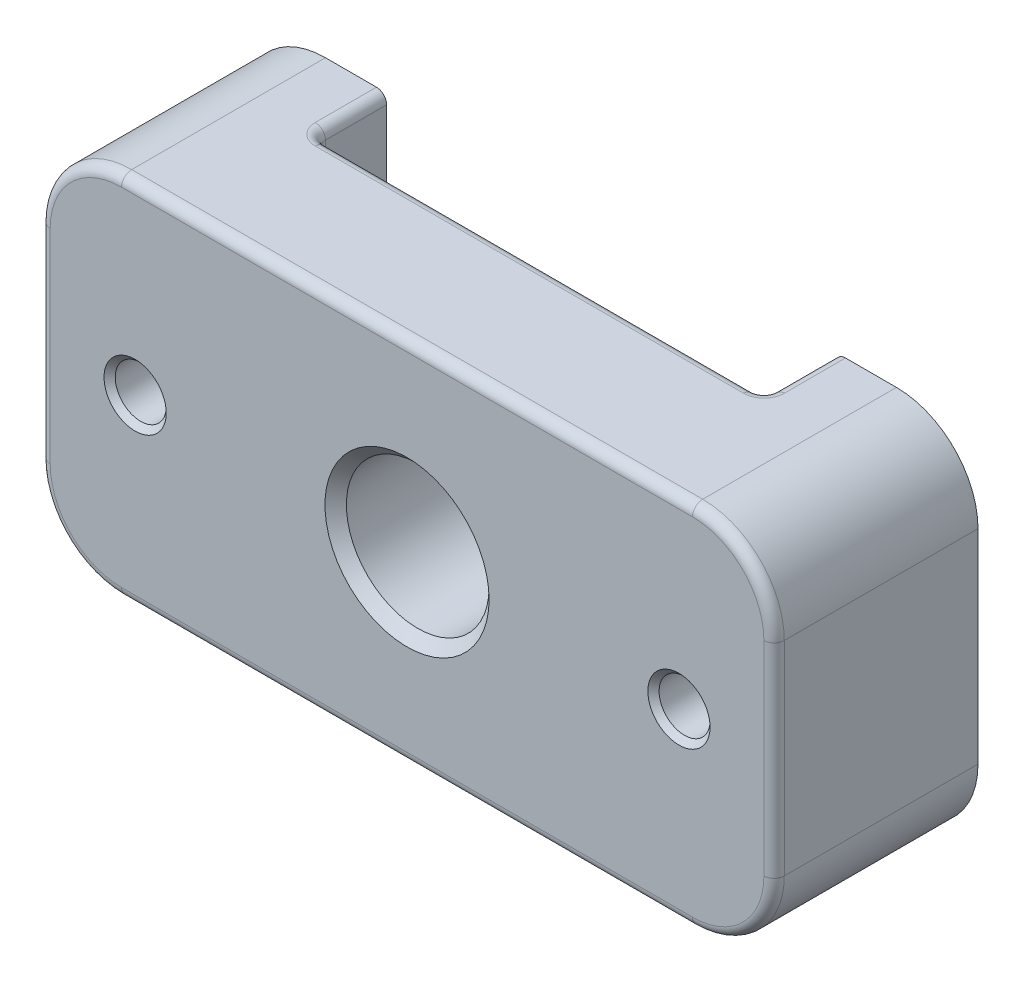
SolidWorks part; units mm, degrees
ref_plane "Front Plane" through (0, 0, 0) normal (0, 0, 1) x (1, 0, 0)
ref_plane "Top Plane" through (0, 0, 0) normal (0, 1, 0) x (1, 0, 0)
ref_plane "Right Plane" through (0, 0, 0) normal (1, 0, 0) x (0, 0, -1)
sketch "Sketch1" plane through (0, 0, 0) normal (0, 0, 1) x (1, 0, 0)
  line L0 (0, 9) -> (0, 13.2219) construction
  line L1 (-14, 9.1417) -> (14, 9.1417)
  line L2 (-18, 5.1417) -> (-18, -4.8583)
  line L3 (-14, -8.8583) -> (14, -8.8583)
  line L4 (18, 5.1417) -> (18, -4.8583)
  line L5 (-18, 9.1417) -> (18, -8.8583) construction
  line L6 (-18, -8.8583) -> (18, 9.1417) construction
  arc A3 (14, 9.1417) -> (18, 5.1417) centre (14, 5.1417) cw
  arc A4 (14, -8.8583) -> (18, -4.8583) centre (14, -4.8583) ccw
  arc A5 (-18, -4.8583) -> (-14, -8.8583) centre (-14, -4.8583) ccw
  arc A6 (-14, 9.1417) -> (-18, 5.1417) centre (-14, 5.1417) ccw
  dimension "D1" = 36
  dimension "D2" = 18
  dimension "D4" = 4
extrude "Boss-Extrude1" add sketch "Sketch1" along normal blind 10
sketch "Sketch5" plane through (0, 9.1417, 0) normal (0, 1, 0) x (1, 0, 0)
  line L1 (-11, 3.5) -> (11, 3.5)
  line L2 (-11, 3.5) -> (-11, -3.5)
  line L3 (-11, -3.5) -> (11, -3.5)
  line L4 (11, 3.5) -> (11, -3.5)
  line L5 (-11, 3.5) -> (11, -3.5) construction
  line L6 (-11, -3.5) -> (11, 3.5) construction
  line L7 (14, 0) -> (-14, 0) construction
  point P0 (0, 0)
  dimension "D1" = 22
  dimension "D2" = 3.5
extrude "Cut-Extrude2" cut sketch "Sketch5" against normal through all
fillet "Fillet3" radius 0.5 16 edges at (-11, 0.1417, 3.5) (0, -8.8583, 3.5) (11, 0.1417, 3.5) (0, 9.1417, 3.5) (-11, -8.8583, 1.75) (11, -8.8583, 1.75) (11, 9.1417, 1.75) (-11, 9.1417, 1.75) (16.8284, 7.9702, 10) (18, 0.1417, 10) (16.8284, -7.6867, 10) (0, -8.8583, 10) (-16.8284, -7.6867, 10) (-18, 0.1417, 10) (-16.8284, 7.9702, 10) (0, 9.1417, 10)
hole_wizard "M3x0.5 Tapped Hole1" positions "3DSketch1" profile "Sketch6" tap size "M3x0.5" standard "ANSI Metric" end condition through all
sketch3d "3DSketch1"
  line L0 (-13.335, 0.1417, 10) -> (13.335, 0.1417, 10) construction
  point P0 (-13.335, 0.1417, 10)
  point P2 (13.335, 0.1417, 10)
  point P8 (0, 0.1417, 10)
  point P9 (0, 0, 0)
  dimension "D1" = 9
  dimension "D2" = 9
  dimension "D3" = 26.67
sketch "Sketch6" plane through (-13.335, 0.1417, 10) normal (1, 0, 0) x (0, -1, 0)
  line L0 (0, 0) -> (0, 10)
  line L1 (0, 10) -> (1.25, 10)
  line L2 (1.25, 10) -> (1.25, 0.275)
  line L3 (1.25, 0.275) -> (1.525, 0)
  line L5 (1.525, 0) -> (0, 0)
  line L6 (-1.25, 0.275) -> (-1.525, 0) construction
  line L11 (0, -6.35) -> (0, 107.95) construction
  dimension "Thru Tap Drill Dia." = 2.5
  dimension "Thru Tap Drill Depth" = 10
  dimension "Near C'Sink Dia." = 3.05
  dimension "Near C'Sink Angle" = 90
cosmetic thread "Hole Thread1" parameters "D2"=3
cosmetic thread "Hole Thread2" parameters "D2"=3
hole_wizard "M8x1.0 Tapped Hole1" positions "3DSketch2" profile "Sketch7" tap size "M8x1.0" standard "ANSI Metric" end condition through all
sketch3d "3DSketch2"
  point P0 (0, 0.1417, 10)
  dimension "D1" = 9
  dimension "D2" = 18
sketch "Sketch7" plane through (0, 0.1417, 10) normal (1, 0, 0) x (0, -1, 0)
  line L0 (0, 0) -> (0, 10)
  line L1 (0, 10) -> (3.5, 10)
  line L2 (3.5, 10) -> (3.5, 0.525)
  line L3 (3.5, 0.525) -> (4.025, 0)
  line L5 (4.025, 0) -> (0, 0)
  line L6 (-3.5, 0.525) -> (-4.025, 0) construction
  line L11 (0, -6.35) -> (0, 107.95) construction
  dimension "Thru Tap Drill Dia." = 7
  dimension "Thru Tap Drill Depth" = 10
  dimension "Near C'Sink Dia." = 8.05
  dimension "Near C'Sink Angle" = 90
cosmetic thread "Hole Thread3" parameters "D2"=8
